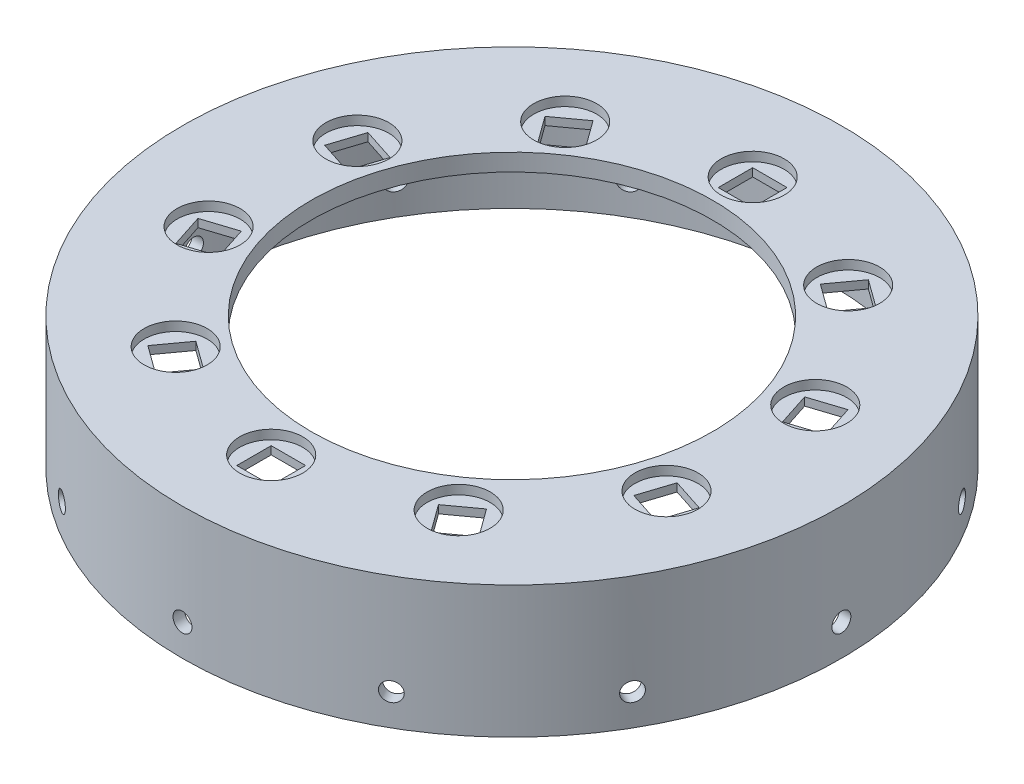
SolidWorks part; units mm, degrees
ref_plane "Front Plane" through (0, 0, 0) normal (0, 0, 1) x (1, 0, 0)
ref_plane "Top Plane" through (0, 0, 0) normal (0, 1, 0) x (1, 0, 0)
ref_plane "Right Plane" through (0, 0, 0) normal (1, 0, 0) x (0, 0, -1)
sketch "Sketch1" plane through (0, 0, 0) normal (0, 1, 0) x (1, 0, 0)
  circle A0 centre (0, 0) radius 55.5
  circle A1 centre (0, 0) radius 57.5
  dimension "D1" = 111
  dimension "D2" = 2
extrude "Boss-Extrude1" add sketch "Sketch1" along normal blind 20
sketch "Sketch2" plane through (0, 20, 0) normal (0, 1, 0) x (1, 0, 0)
  circle A0 centre (0, 0) radius 57.5 construction
  circle A1 centre (0, 0) radius 57.5
  circle A2 centre (0, 0) radius 35
  point P5 (0, 0)
  dimension "D1" = 70
extrude "Boss-Extrude2" add sketch "Sketch2" along normal blind 3
sketch "Sketch3" plane through (0, 23, 0) normal (0, 1, 0) x (1, 0, 0)
  line L0 (0, 0) -> (0, -42) construction
  circle A0 centre (0, -42) radius 5.5
  dimension "D1" = 11
  dimension "D2" = 42
extrude "Cut-Extrude1" cut sketch "Sketch3" against normal blind 1.6
sketch "Sketch4" plane through (0, 21.4, 0) normal (0, 1, 0) x (1, 0, 0)
  line L1 (-3, -39) -> (3, -39)
  line L2 (-3, -39) -> (-3, -45)
  line L3 (-3, -45) -> (3, -45)
  line L4 (3, -39) -> (3, -45)
  line L5 (-3, -39) -> (3, -45) construction
  line L6 (-3, -45) -> (3, -39) construction
  point P0 (0, -42)
  point P1 (0, -42)
  dimension "D1" = 6
extrude "Cut-Extrude2" cut sketch "Sketch4" against normal through all
pattern_circular "CirPattern1" count 10 over 360 about axis through (0, 0, 0) along (0, 1, 0) of "Cut-Extrude1", "Cut-Extrude2"
sketch "Sketch5" plane through (0, 0, 0) normal (0, 0, 1) x (1, 0, 0)
  line L0 (0, 5.5) -> (0, 0) construction
  line L1 (-55.5, 20) -> (55.5, 20) construction
  line L2 (-55.5, 20) -> (55.5, 20) construction
  circle A0 centre (0, 5.5) radius 1.65
  dimension "D1" = 3.3
  dimension "D2" = 14.5
extrude "Cut-Extrude3" cut sketch "Sketch5" against normal through all
pattern_circular "CirPattern2" count 12 over 360 about axis through (0, 20, 0) along (0, -1, 0) of "Cut-Extrude3"
fillet "Fillet1" radius 1 1 edges at (0, 20, 55.5)
